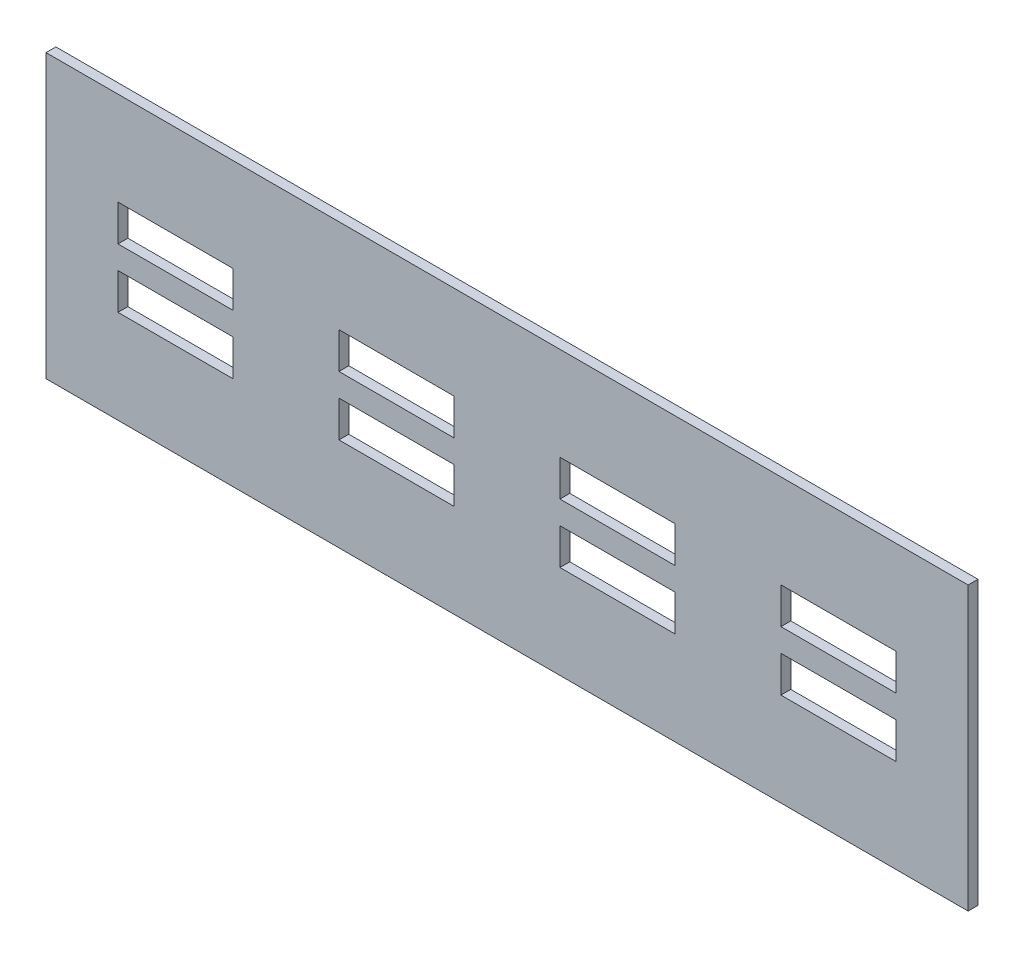
SolidWorks part; units mm, degrees
ref_plane "Plano frontal" through (0, 0, 0) normal (0, 0, 1) x (1, 0, 0)
ref_plane "Plano superior" through (0, 0, 0) normal (0, 1, 0) x (1, 0, 0)
ref_plane "Plano direito" through (0, 0, 0) normal (1, 0, 0) x (0, 0, -1)
sketch "Esboço1" plane through (0, 0, 0) normal (0, 0, 1) x (1, 0, 0)
  line L1 (-140, 55) -> (140, 55)
  line L2 (-140, 55) -> (-140, -30.764)
  line L3 (-140, -30.764) -> (140, -30.764)
  line L4 (140, 55) -> (140, -30.764)
extrude "Ressalto-extrusão1" add sketch "Esboço1" along normal blind 3
sketch "Esboço2" plane through (0, 0, 3) normal (0, 0, 1) x (1, 0, 0)
  line L0 (0, 85.6145) -> (0, -111.412) construction
  line L1 (-192.9122, 12.12) -> (-134.2, 12.12) construction
  line L2 (140, 55) -> (-140, 55) construction
  line L3 (67.1, 85.6145) -> (67.1, -111.412) construction
  line L4 (33.55, 85.6145) -> (33.55, 15.62) construction
  line L5 (-67.1, 85.6145) -> (-67.1, -111.412) construction
  line L6 (134.2, 85.6145) -> (134.2, -111.412) construction
  line L7 (-33.55, 85.6145) -> (-33.55, 15.62) construction
  line L8 (-134.2, 85.6145) -> (-134.2, -111.412) construction
  line L9 (100.65, 85.6145) -> (100.65, 15.62) construction
  line L10 (-100.65, 85.6145) -> (-100.65, 12.12) construction
  line L11 (-118.15, 15.62) -> (-118.15, 26.62)
  line L12 (83.15, -2.38) -> (118.15, -2.38)
  line L13 (83.15, -2.38) -> (83.15, 8.62)
  line L14 (83.15, 26.62) -> (118.15, 26.62)
  line L15 (118.15, -2.38) -> (118.15, 8.62)
  line L16 (83.15, -2.38) -> (100.65, 12.12) construction
  line L17 (83.15, 26.62) -> (96.4259, 15.62) construction
  line L18 (16.05, -2.38) -> (51.05, -2.38)
  line L19 (16.05, -2.38) -> (16.05, 8.62)
  line L20 (16.05, 26.62) -> (51.05, 26.62)
  line L21 (51.05, -2.38) -> (51.05, 8.62)
  line L22 (16.05, -2.38) -> (29.3259, 8.62) construction
  line L23 (16.05, 26.62) -> (29.3259, 15.62) construction
  line L24 (-51.05, -2.38) -> (-16.05, -2.38)
  line L25 (-51.05, -2.38) -> (-51.05, 8.62)
  line L26 (-51.05, 26.62) -> (-16.05, 26.62)
  line L27 (-16.05, -2.38) -> (-16.05, 8.62)
  line L28 (-51.05, -2.38) -> (-37.7741, 8.62) construction
  line L29 (-51.05, 26.62) -> (-37.7741, 15.62) construction
  line L30 (-118.15, -2.38) -> (-83.15, -2.38)
  line L31 (-118.15, -2.38) -> (-118.15, 8.62)
  line L32 (-118.15, 26.62) -> (-83.15, 26.62)
  line L33 (-83.15, -2.38) -> (-83.15, 8.62)
  line L34 (-118.15, -2.38) -> (-104.8741, 8.62) construction
  line L35 (-118.15, 26.62) -> (-100.65, 12.12) construction
  line L36 (83.15, 8.62) -> (118.15, 8.62)
  line L38 (83.15, 15.62) -> (118.15, 15.62)
  line L40 (83.15, 8.62) -> (100.65, 12.12) construction
  line L41 (100.65, 12.12) -> (118.15, 8.62) construction
  line L42 (16.05, 8.62) -> (51.05, 8.62)
  line L44 (16.05, 15.62) -> (51.05, 15.62)
  line L46 (83.15, 15.62) -> (83.15, 26.62)
  line L47 (100.65, 12.12) -> (118.15, -2.38) construction
  line L48 (-51.05, 8.62) -> (-16.05, 8.62)
  line L50 (-51.05, 15.62) -> (-16.05, 15.62)
  line L52 (16.05, 15.62) -> (16.05, 26.62)
  line L53 (37.7741, 8.62) -> (51.05, -2.38) construction
  line L54 (-118.15, 8.62) -> (-83.15, 8.62)
  line L56 (-118.15, 15.62) -> (-83.15, 15.62)
  line L58 (-100.65, 12.12) -> (-83.15, 15.62) construction
  line L59 (-118.15, 15.62) -> (-100.65, 12.12) construction
  line L60 (-100.65, 12.12) -> (-83.15, 26.62) construction
  line L61 (-100.65, 8.62) -> (-100.65, -111.412) construction
  line L62 (-96.4259, 8.62) -> (-83.15, -2.38) construction
  line L63 (-67.1, 12.12) -> (-16.05, 12.12) construction
  line L64 (-83.15, 15.62) -> (-83.15, 26.62)
  line L65 (-118.15, 12.12) -> (-100.65, 12.12) construction
  line L66 (-51.05, 15.62) -> (-51.05, 26.62)
  line L67 (-29.3259, 8.62) -> (-16.05, -2.38) construction
  line L68 (-33.55, 8.62) -> (-33.55, -111.412) construction
  line L69 (-29.3259, 15.62) -> (-16.05, 26.62) construction
  line L70 (-16.05, 15.62) -> (-16.05, 26.62)
  line L71 (0, 12.12) -> (51.05, 12.12) construction
  line L72 (33.55, 8.62) -> (33.55, -111.412) construction
  line L73 (37.7741, 15.62) -> (51.05, 26.62) construction
  line L74 (51.05, 15.62) -> (51.05, 26.62)
  line L75 (83.15, 12.12) -> (100.65, 12.12) construction
  line L76 (100.65, 12.12) -> (100.65, -111.412) construction
  line L77 (104.8741, 15.62) -> (118.15, 26.62) construction
  line L78 (118.15, 15.62) -> (118.15, 26.62)
  line L79 (134.2, 12.12) -> (182.3981, 12.12) construction
  point P23 (100.65, 12.12)
  point P28 (33.55, 12.12)
  point P33 (-33.55, 12.12)
  point P38 (-100.65, 12.12)
  point P43 (100.65, 12.12)
  point P48 (33.55, 12.12)
  point P53 (-33.55, 12.12)
  point P58 (-100.65, 12.12)
  dimension "D1" = 42.88
  dimension "D2" = 67.1
  dimension "D3" = 67.1
  dimension "D4" = 67.1
  dimension "D5" = 67.1
  dimension "D6" = 33.55
  dimension "D7" = 33.55
  dimension "D8" = 33.55
  dimension "D9" = 33.55
  dimension "D10" = 35
  dimension "D11" = 29
  dimension "D12" = 7
  dimension "D13" = 35
  dimension "D14" = 29
  dimension "D15" = 7
  dimension "D16" = 35
  dimension "D17" = 29
  dimension "D18" = 7
  dimension "D19" = 35
  dimension "D20" = 29
  dimension "D21" = 7
extrude "Corte-extrusão1" cut sketch "Esboço2" against normal up to surface (3 mm away) up to face at (0, 12.118, 0)
